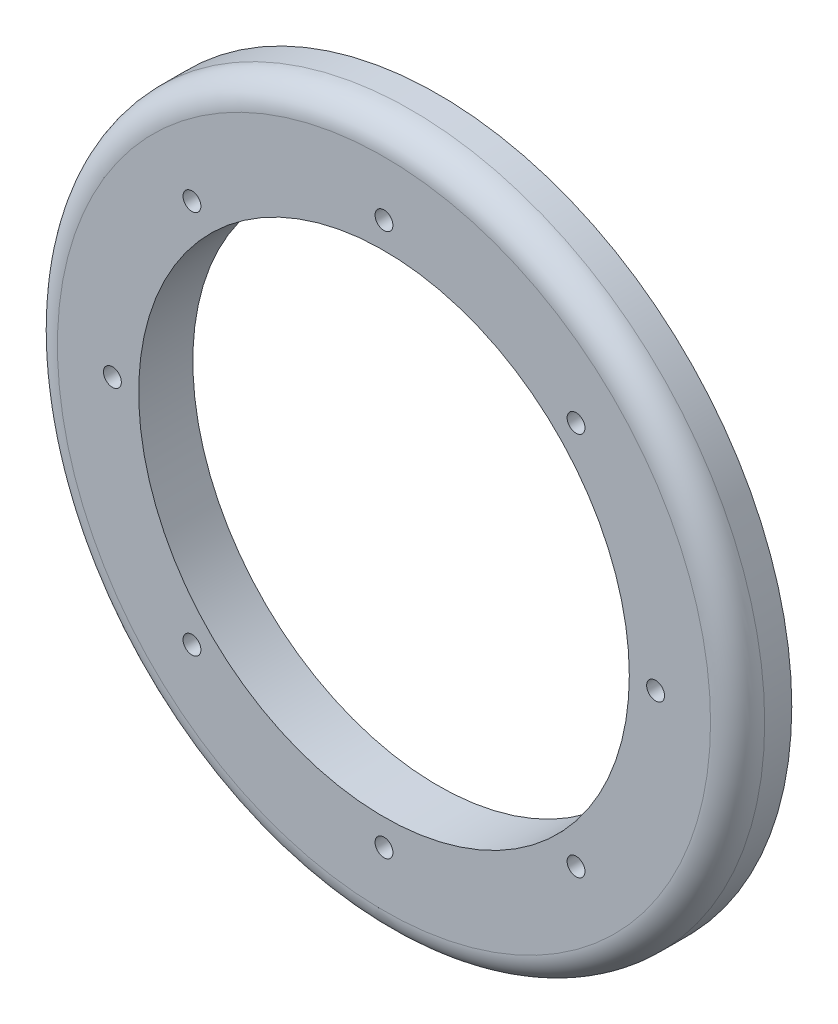
SolidWorks part; units mm, degrees
ref_plane "Front Plane" through (0, 0, 0) normal (0, 0, 1) x (1, 0, 0)
ref_plane "Top Plane" through (0, 0, 0) normal (0, 1, 0) x (1, 0, 0)
ref_plane "Right Plane" through (0, 0, 0) normal (1, 0, 0) x (0, 0, -1)
sketch "Sketch1" plane through (0, 0, 0) normal (0, 0, 1) x (1, 0, 0)
  circle A0 centre (0, 0) radius 45.3 construction
  circle A1 centre (0, 0) radius 45.3
  circle A2 centre (0, 0) radius 65.3
  circle A3 centre (35.4614, -35.4614) radius 1.65
  circle A7 centre (0, -50.15) radius 1.65
  circle A8 centre (-35.4614, -35.4614) radius 1.65
  circle A9 centre (-50.15, 0) radius 1.65
  circle A10 centre (-35.4614, 35.4614) radius 1.65
  circle A11 centre (0, 50.15) radius 1.65
  circle A12 centre (35.4614, 35.4614) radius 1.65
  circle A13 centre (50.15, 0) radius 1.65
  point P25 (0, 0)
  dimension "D2" = 3.3
  dimension "D1" = 20
  dimension "D3" = 8
extrude "Boss-Extrude1" add sketch "Sketch1" along normal blind 10
fillet "Fillet1" radius 5 1 edges at (65.3, 0, 10)
